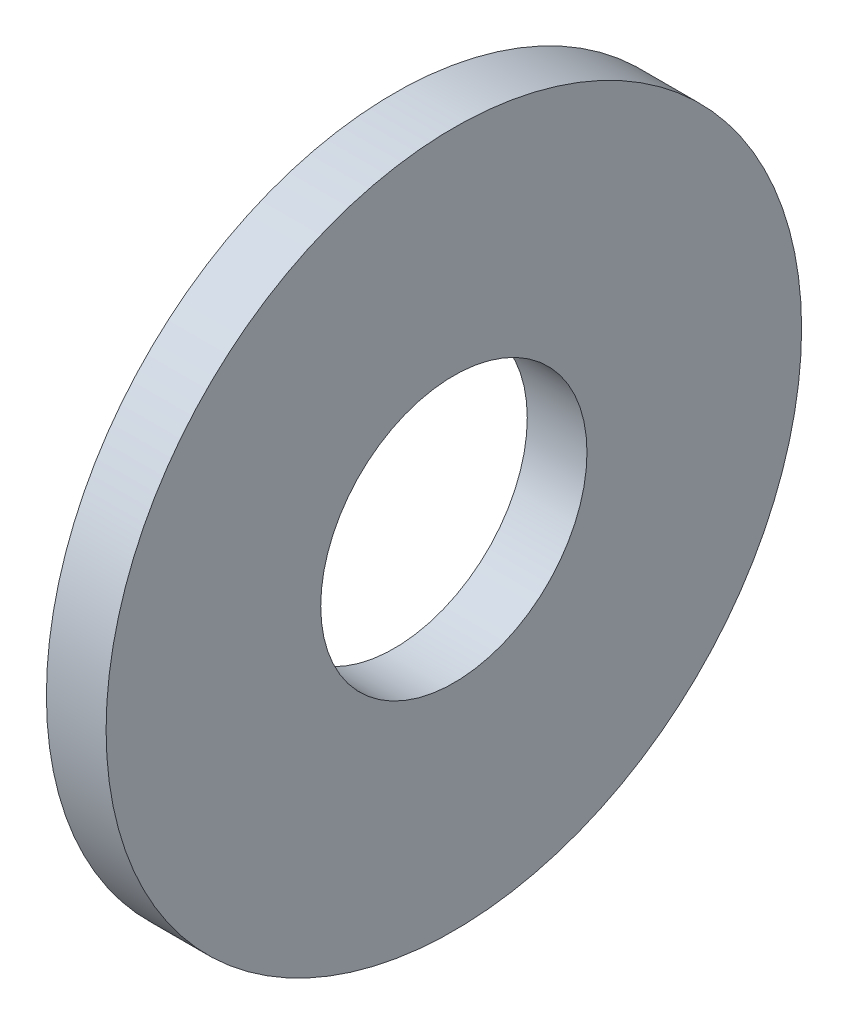
SolidWorks part; units mm, degrees
ref_plane "Plane1" through (0, 0, 0) normal (0, 0, 1) x (1, 0, 0)
ref_plane "Plane2" through (0, 0, 0) normal (0, 1, 0) x (1, 0, 0)
ref_plane "Plane3" through (0, 0, 0) normal (1, 0, 0) x (0, 0, -1)
sketch "Sketch1" plane through (0, 0, 0) normal (0, 0, 1) x (1, 0, 0)
  line L0 (-34.925, 0) -> (9.525, 0) construction
  line L1 (0, 3.5687) -> (0, 9.3218)
  line L2 (0, 9.3218) -> (-1.6002, 9.3218)
  line L3 (-1.6002, 9.3218) -> (-1.6002, 3.5687)
  line L4 (-1.6002, 3.5687) -> (0, 3.5687)
  dimension "Thickness" = 1.6002
  dimension "Inside_dia" = 7.1374
  dimension "Outside_dia" = 18.6436
revolve "Base-Revolve" add sketch "Sketch1" angle 360 about L0
